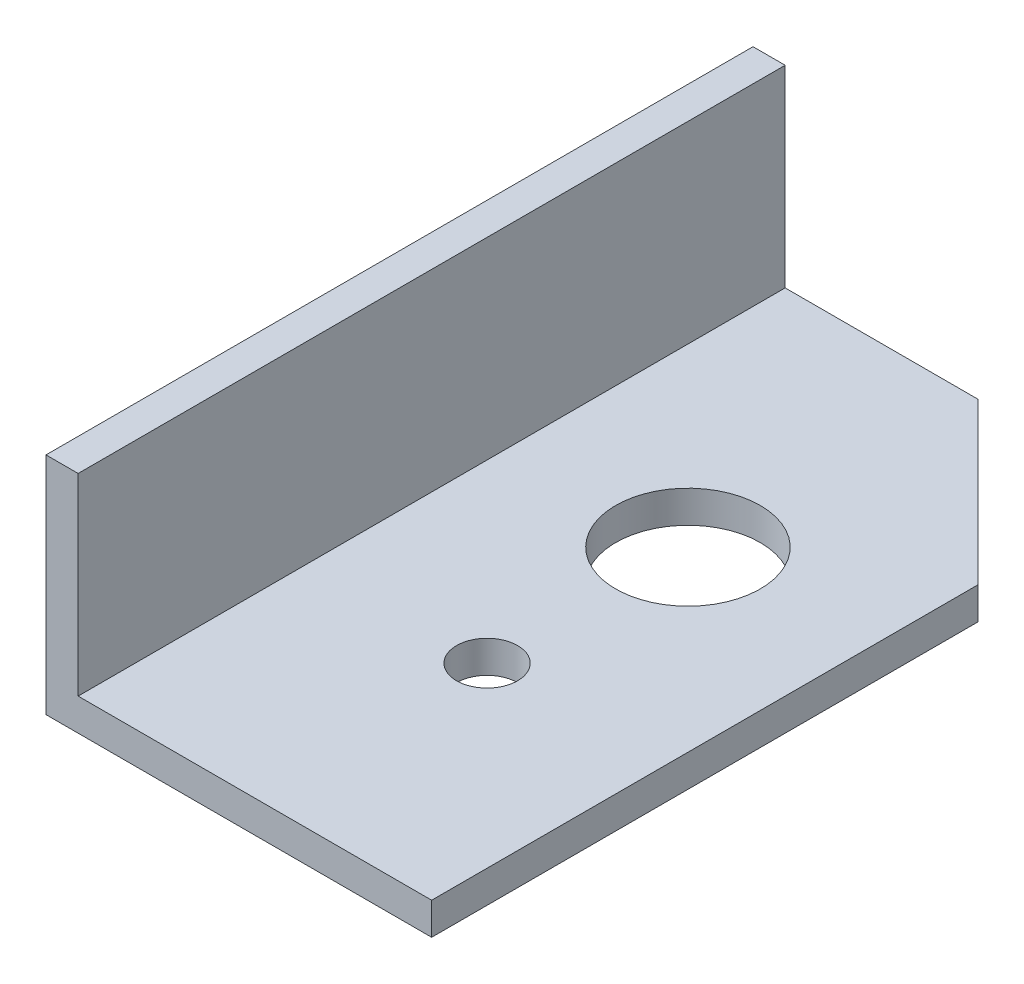
SolidWorks part; units mm, degrees
ref_plane "Спереди" through (0, 0, 0) normal (0, 0, 1) x (1, 0, 0)
ref_plane "Сверху" through (0, 0, 0) normal (0, 1, 0) x (1, 0, 0)
ref_plane "Справа" through (0, 0, 0) normal (1, 0, 0) x (0, 0, -1)
sketch "Эскиз2" plane through (0, 0, 0) normal (0, 0, 1) x (1, 0, 0)
  line L0 (0, 0) -> (0, 14)
  line L1 (0, 0) -> (24, 0)
extrude "Вытянуть-Тонкостенный1" add sketch "Эскиз2" along normal blind 44 thin
chamfer "Фаска1" distance 10 angle 45 1 edges at (24, 1, 0)
sketch "Эскиз4" plane through (0, 2, 0) normal (0, 1, 0) x (-1, 0, 0)
  line L0 (-2, 22) -> (14.8253, 22) construction
  circle A2 centre (-12.95, 17) radius 4.5
  circle A3 centre (-12.95, 29.5) radius 1.9
extrude "Вырез-Вытянуть1" cut sketch "Эскиз4" against normal through all
